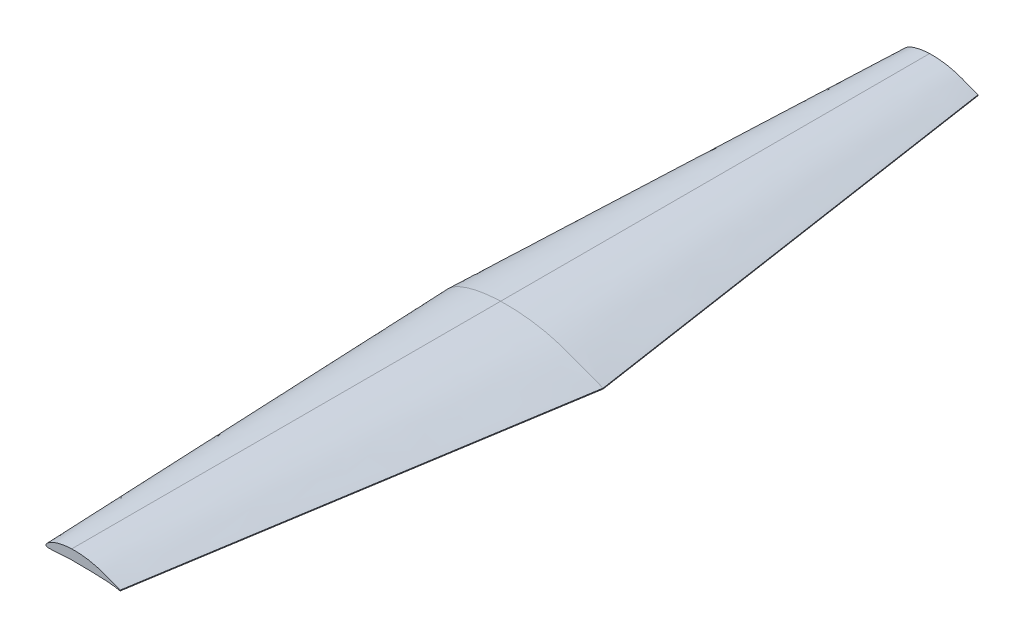
SolidWorks part; units mm, degrees
ref_plane "前视基准面" through (0, 0, 0) normal (0, 0, 1) x (1, 0, 0)
ref_plane "上视基准面" through (0, 0, 0) normal (0, 1, 0) x (1, 0, 0)
ref_plane "右视基准面" through (0, 0, 0) normal (1, 0, 0) x (0, 0, -1)
sketch "草图3" plane through (0, 0, 0) normal (0, 0, 1) x (1, 0, 0)
  line L0 (286.0556, -67.2093) -> (286.0556, -69.5328)
  spline S0 degree 3 poles (0, 0) (-2.7254, 0.1648) (-6.5293, -0.1383) (-11.397, -0.4053) (-15.7139, -0.6444) (-21.1219, -1.0416) (-27.6196, -1.6029) (-34.106, -2.271) (-40.5798, -3.0436) (-47.0383, -3.9317) (-53.4797, -4.936) (-58.8544, -5.8774) (-63.17, -6.7002) (-66.4344, -7.3579) (-69.692, -8.0463) (-72.9411, -8.7726) (-76.1832, -9.53) (-79.4172, -10.3236) (-82.6712, -11.1618) (-85.9452, -12.0414) (-89.2363, -12.971) (-92.5148, -13.9419) (-95.7791, -14.9599) (-99.0288, -16.0242) (-102.2624, -17.1403) (-104.9625, -18.1217) (-107.1365, -18.9452) (-108.7915, -19.5894) (-110.4392, -20.2501) (-112.0802, -20.926) (-113.4364, -21.5146) (-114.7996, -22.0847) (-116.4298, -22.8496) (-118.3603, -23.7346) (-120.2914, -24.6854) (-121.9485, -25.5247) (-123.5937, -26.392) (-125.2295, -27.284) (-126.8556, -28.2049) (-128.5172, -29.1774) (-130.2108, -30.2054) (-131.9305, -31.2916) (-133.6283, -32.4064) (-135.2985, -33.5465) (-136.9327, -34.7128) (-138.5277, -35.8993) (-139.8798, -36.9561) (-141.0061, -37.8695) (-141.9216, -38.6374) (-142.8307, -39.4252) (-143.7397, -40.2392) (-144.6561, -41.086) (-145.5864, -41.9717) (-146.6414, -43.0038) (-147.814, -44.1864) (-149.0511, -45.5345) (-150.1833, -46.9378) (-151.1378, -48.3803) (-151.8357, -49.854) (-152.198, -51.3579) (-152.1164, -52.6852) (-151.7365, -53.7579) (-151.2487, -54.6228) (-150.6211, -55.445) (-149.8757, -56.2108) (-149.0412, -56.9109) (-148.1414, -57.5317) (-147.2349, -58.0421) (-146.3423, -58.4466) (-145.4769, -58.7603) (-144.6033, -59.0093) (-143.7243, -59.2082) (-142.8393, -59.3636) (-141.9506, -59.4905) (-140.8259, -59.6225) (-139.4649, -59.7643) (-137.8658, -59.9018) (-136.2622, -60.0125) (-134.6556, -60.0983) (-133.0466, -60.1615) (-131.4364, -60.2023) (-129.8251, -60.2236) (-128.2132, -60.2252) (-126.6017, -60.2114) (-124.9913, -60.1828) (-123.3818, -60.1442) (-121.7725, -60.0943) (-120.1633, -60.0396) (-118.5533, -59.9787) (-116.4051, -59.8971) (-114.2563, -59.8096) (-112.1077, -59.7183) (-110.4961, -59.646) (-108.8842, -59.573) (-106.7339, -59.4685) (-104.0451, -59.3331) (-100.8189, -59.158) (-97.5935, -58.9743) (-94.369, -58.7831) (-91.1445, -58.5883) (-87.9195, -58.3917) (-84.6944, -58.1934) (-81.4687, -57.9986) (-78.2436, -57.8034) (-75.0185, -57.6121) (-71.7936, -57.4231) (-68.568, -57.2395) (-65.3421, -57.0559) (-60.8897, -56.812) (-50.4824, -56.2568) (-39.738, -55.7609) (-29.1456, -55.3181) (-23.4361, -55.1001) (-16.9891, -54.8712) (-10.5445, -54.6675) (-5.2161, -54.5116) (24.8162, -53.7512) (54.8641, -53.7858) (86.0077, -54.1717) (92.4374, -54.2674) (98.866, -54.378) (104.7346, -54.4925) (115.4929, -54.7248) (126.2066, -55.0005) (137.478, -55.3335) (143.8594, -55.5311) (149.2135, -55.7021) (153.497, -55.8457) (156.069, -55.93) (159.2825, -56.0398) (163.5676, -56.1844) (169.5643, -56.3927) (175.9899, -56.6246) (182.4135, -56.8749) (188.8353, -57.1505) (195.2555, -57.456) (201.6747, -57.8026) (208.0953, -58.1948) (214.5156, -58.6401) (220.934, -59.1451) (227.3471, -59.7063) (233.7544, -60.3361) (240.1564, -61.0305) (246.5529, -61.799) (251.8849, -62.5035) (256.1556, -63.107) (259.3661, -63.5886) (262.5702, -64.1028) (265.7667, -64.6553) (268.953, -65.255) (272.1283, -65.9071) (275.3111, -66.6228) (278.4998, -67.4069) (282.0905, -68.3717) (284.6152, -69.0618) (286.0556, -69.5328) knots 0 0 0 0 0.013429 0.018717 0.024004 0.034706 0.045405 0.056103 0.066798 0.077493 0.088187 0.098883 0.104347 0.10981 0.115272 0.120733 0.126196 0.131659 0.137123 0.142734 0.148344 0.153954 0.159562 0.165173 0.170784 0.176398 0.179312 0.182225 0.185139 0.188049 0.19096 0.192415 0.195321 0.199821 0.202867 0.205915 0.208964 0.21202 0.215085 0.218161 0.221496 0.224835 0.228171 0.231492 0.234788 0.238052 0.241275 0.243233 0.245189 0.247156 0.249154 0.251194 0.253297 0.255475 0.258458 0.261493 0.264477 0.267324 0.269988 0.272465 0.274861 0.276409 0.278031 0.279729 0.281486 0.283281 0.285082 0.286859 0.288394 0.2899 0.291385 0.292861 0.294334 0.295807 0.297279 0.299907 0.302541 0.305178 0.307818 0.31046 0.313103 0.315746 0.318391 0.321036 0.323677 0.326318 0.32896 0.331601 0.334243 0.33689 0.342182 0.344828 0.347475 0.350122 0.352769 0.358071 0.363372 0.368672 0.373971 0.379271 0.384571 0.389873 0.395175 0.400476 0.405775 0.411076 0.416376 0.421677 0.426979 0.438322 0.472972 0.479916 0.490502 0.501094 0.511666 0.522237 0.52733 0.659527 0.670078 0.680626 0.691176 0.701723 0.709516 0.744139 0.754471 0.765016 0.775562 0.780836 0.78611 0.788228 0.796661 0.807212 0.81776 0.828308 0.838852 0.849396 0.859942 0.870492 0.881056 0.891618 0.902179 0.91274 0.923304 0.933873 0.944448 0.949775 0.955101 0.960426 0.965747 0.971066 0.976383 0.9817 0.987121 0.992543 1 1 1 1
  spline S1 degree 3 poles (286.0556, -67.2093) (284.6443, -66.5978) (282.1755, -65.5473) (278.6409, -64.0767) (275.4746, -62.7904) (272.3122, -61.5438) (269.1569, -60.3294) (265.9937, -59.1363) (262.8244, -57.9585) (259.6502, -56.7935) (256.4744, -55.631) (252.2394, -54.0827) (246.9511, -52.1365) (240.6147, -49.781) (234.284, -47.4153) (227.9569, -45.0405) (221.6324, -42.6584) (215.3064, -40.2746) (208.9898, -37.8949) (202.6812, -35.5252) (196.3783, -33.1767) (190.0656, -30.8589) (183.9614, -28.6584) (179.5601, -27.1217) (176.6075, -26.0994) (174.2596, -25.3115) (170.1866, -23.92) (166.2258, -22.6238) (161.874, -21.285) (158.7366, -20.2915) (155.0668, -19.2273) (150.9749, -18.0061) (145.689, -16.5449) (139.3271, -14.8623) (132.9397, -13.2769) (126.5291, -11.7843) (120.1314, -10.3953) (113.7497, -9.1072) (107.3863, -7.9187) (101.0078, -6.8208) (94.6155, -5.8053) (88.2098, -4.8761) (81.7918, -4.0266) (75.3764, -3.2568) (68.9655, -2.5621) (62.5612, -1.9454) (56.1516, -1.404) (49.7366, -0.9395) (43.3162, -0.5533) (36.8905, -0.2441) (30.4575, -0.0157) (24.0193, 0.1343) (17.5776, 0.2001) (9.5705, 0.1861) (3.7124, 0.0371) (0, 0) knots 0 0 0 0 0.015566 0.027153 0.038744 0.050153 0.061555 0.072961 0.084369 0.095774 0.107181 0.118595 0.141408 0.164211 0.187011 0.209806 0.232607 0.255409 0.278224 0.30092 0.323611 0.346297 0.368978 0.389281 0.393477 0.4006 0.414345 0.437038 0.442772 0.460425 0.470342 0.481442 0.503641 0.525841 0.548041 0.570244 0.592452 0.614296 0.636131 0.657965 0.679798 0.701634 0.723471 0.745317 0.767026 0.788731 0.81043 0.832124 0.853822 0.875524 0.89723 0.918967 0.940698 0.962427 1 1 1 1
ref_plane "基准面6" through (0, 0, 1198) normal (0, 0, 1) x (1, 0, 0)
sketch "草图5" plane through (0, 0, 1198) normal (0, 0, 1) x (1, 0, 0)
  line L0 (135.2099, -32.178) -> (134.1595, -31.7343)
  line L1 (134.1595, -31.7343) -> (132.3785, -31.0014)
  line L2 (132.3785, -31.0014) -> (130.538, -30.2628)
  line L3 (130.538, -30.2628) -> (128.6487, -29.5234)
  line L4 (128.6487, -29.5234) -> (126.7095, -28.7801)
  line L5 (126.7095, -28.7801) -> (124.7288, -28.0303)
  line L6 (124.7288, -28.0303) -> (122.7145, -27.2731)
  line L7 (122.7145, -27.2731) -> (120.681, -26.5057)
  line L8 (120.681, -26.5057) -> (118.6366, -25.7333)
  line L9 (118.6366, -25.7333) -> (116.5882, -24.9552)
  line L10 (116.5882, -24.9552) -> (114.5327, -24.1718)
  line L11 (114.5327, -24.1718) -> (112.4767, -23.3864)
  line L12 (112.4767, -23.3864) -> (110.4226, -22.5988)
  line L13 (110.4226, -22.5988) -> (108.3692, -21.8105)
  line L14 (108.3692, -21.8105) -> (106.3231, -21.0245)
  line L15 (106.3231, -21.0245) -> (104.2886, -20.2409)
  line L16 (104.2886, -20.2409) -> (102.2624, -19.4627)
  line L17 (102.2624, -19.4627) -> (100.2393, -18.6847)
  line L18 (100.2393, -18.6847) -> (98.2143, -17.9078)
  line L19 (98.2143, -17.9078) -> (96.1873, -17.1346)
  line L20 (96.1873, -17.1346) -> (94.1685, -16.3685)
  line L21 (94.1685, -16.3685) -> (92.1597, -15.6135)
  line L22 (92.1597, -15.6135) -> (90.1625, -14.8708)
  line L23 (90.1625, -14.8708) -> (88.181, -14.1457)
  line L24 (88.181, -14.1457) -> (86.2061, -13.4369)
  line L25 (86.2061, -13.4369) -> (84.2421, -12.7442)
  line L26 (84.2421, -12.7442) -> (82.2899, -12.0718)
  line L27 (82.2899, -12.0718) -> (80.3415, -11.4207)
  line L28 (80.3415, -11.4207) -> (78.3954, -10.7857)
  line L29 (78.3954, -10.7857) -> (76.4548, -10.1739)
  line L30 (76.4548, -10.1739) -> (74.509, -9.5797)
  line L31 (74.509, -9.5797) -> (72.5628, -9.0033)
  line L32 (72.5628, -9.0033) -> (70.6155, -8.4473)
  line L33 (70.6155, -8.4473) -> (68.6635, -7.9102)
  line L34 (68.6635, -7.9102) -> (66.7063, -7.3907)
  line L35 (66.7063, -7.3907) -> (64.7481, -6.8897)
  line L36 (64.7481, -6.8897) -> (62.7857, -6.4088)
  line L37 (62.7857, -6.4088) -> (60.8187, -5.945)
  line L38 (60.8187, -5.945) -> (58.8481, -5.502)
  line L39 (58.8481, -5.502) -> (56.8722, -5.0759)
  line L40 (56.8722, -5.0759) -> (54.891, -4.67)
  line L41 (54.891, -4.67) -> (52.9027, -4.2816)
  line L42 (52.9027, -4.2816) -> (50.9072, -3.9113)
  line L43 (50.9072, -3.9113) -> (48.906, -3.5568)
  line L44 (48.906, -3.5568) -> (46.9012, -3.2218)
  line L45 (46.9012, -3.2218) -> (44.8875, -2.9037)
  line L46 (44.8875, -2.9037) -> (42.8649, -2.6024)
  line L47 (42.8649, -2.6024) -> (40.8378, -2.3156)
  line L48 (40.8378, -2.3156) -> (38.8054, -2.0458)
  line L49 (38.8054, -2.0458) -> (36.7699, -1.7907)
  line L50 (36.7699, -1.7907) -> (34.7309, -1.5534)
  line L51 (34.7309, -1.5534) -> (32.6898, -1.3307)
  line L52 (32.6898, -1.3307) -> (30.6467, -1.1252)
  line L53 (30.6467, -1.1252) -> (28.6014, -0.935)
  line L54 (28.6014, -0.935) -> (26.5583, -0.7623)
  line L55 (26.5583, -0.7623) -> (24.5119, -0.6066)
  line L56 (24.5119, -0.6066) -> (22.4653, -0.4651)
  line L57 (22.4653, -0.4651) -> (20.4208, -0.3423)
  line L58 (20.4208, -0.3423) -> (18.3735, -0.236)
  line L59 (18.3735, -0.236) -> (16.3292, -0.1453)
  line L60 (16.3292, -0.1453) -> (14.2863, -0.0737)
  line L61 (14.2863, -0.0737) -> (12.2413, -0.0176)
  line L62 (12.2413, -0.0176) -> (10.2028, 0.021)
  line L63 (10.2028, 0.021) -> (8.1626, 0.0399)
  line L64 (8.1626, 0.0399) -> (6.1247, 0.0438)
  line L65 (6.1247, 0.0438) -> (4.0913, 0.0283)
  line L66 (0.0002, 0) -> (-4.574, -0.0878)
  line L67 (-4.574, -0.0878) -> (-6.5869, -0.2357)
  line L68 (-6.5869, -0.2357) -> (-8.5967, -0.4036)
  line L69 (-8.5967, -0.4036) -> (-10.6009, -0.5882)
  line L70 (-10.6009, -0.5882) -> (-12.5959, -0.7929)
  line L71 (-12.5959, -0.7929) -> (-14.5847, -1.0176)
  line L72 (-14.5847, -1.0176) -> (-16.5631, -1.2611)
  line L73 (-16.5631, -1.2611) -> (-18.5329, -1.5264)
  line L74 (-18.5329, -1.5264) -> (-20.4942, -1.8124)
  line L75 (-20.4942, -1.8124) -> (-22.4457, -2.1198)
  line L76 (-22.4457, -2.1198) -> (-24.3887, -2.4489)
  line L77 (-24.3887, -2.4489) -> (-26.3213, -2.8001)
  line L78 (-26.3213, -2.8001) -> (-28.246, -3.1737)
  line L79 (-28.246, -3.1737) -> (-30.1572, -3.568)
  line L80 (-30.1572, -3.568) -> (-32.0588, -3.9874)
  line L81 (-32.0588, -3.9874) -> (-33.9481, -4.4282)
  line L82 (-33.9481, -4.4282) -> (-35.8246, -4.8922)
  line L83 (-35.8246, -4.8922) -> (-37.6857, -5.3777)
  line L84 (-37.6857, -5.3777) -> (-39.5304, -5.886)
  line L85 (-39.5304, -5.886) -> (-41.3497, -6.4123)
  line L86 (-41.3497, -6.4123) -> (-43.1433, -6.9624)
  line L87 (-43.1433, -6.9624) -> (-44.9092, -7.5318)
  line L88 (-44.9092, -7.5318) -> (-46.6407, -8.124)
  line L89 (-46.6407, -8.124) -> (-48.3382, -8.7359)
  line L90 (-48.3382, -8.7359) -> (-49.9933, -9.367)
  line L91 (-49.9933, -9.367) -> (-51.6046, -10.0187)
  line L92 (-51.6046, -10.0187) -> (-53.1677, -10.6886)
  line L93 (-53.1677, -10.6886) -> (-54.6759, -11.3734)
  line L94 (-54.6759, -11.3734) -> (-56.1242, -12.0786)
  line L95 (-56.1242, -12.0786) -> (-57.5169, -12.7992)
  line L96 (-57.5169, -12.7992) -> (-58.8452, -13.53)
  line L97 (-58.8452, -13.53) -> (-60.1046, -14.2643)
  line L98 (-60.1046, -14.2643) -> (-61.2879, -14.995)
  line L99 (-61.2879, -14.995) -> (-62.3893, -15.711)
  line L100 (-62.3893, -15.711) -> (-63.403, -16.4041)
  line L101 (-63.403, -16.4041) -> (-64.3262, -17.0669)
  line L102 (-64.3262, -17.0669) -> (-65.1602, -17.6981)
  line L103 (-65.1602, -17.6981) -> (-65.9115, -18.2938)
  line L104 (-65.9115, -18.2938) -> (-66.5852, -18.8526)
  line L105 (-66.5852, -18.8526) -> (-67.188, -19.3779)
  line L106 (-67.188, -19.3779) -> (-67.7286, -19.8695)
  line L107 (-67.7286, -19.8695) -> (-68.2151, -20.3272)
  line L108 (-68.2151, -20.3272) -> (-68.6531, -20.7544)
  line L109 (-68.6531, -20.7544) -> (-69.0499, -21.1521)
  line L110 (-69.0499, -21.1521) -> (-69.4107, -21.5226)
  line L111 (-69.4107, -21.5226) -> (-69.7393, -21.8688)
  line L112 (-69.7393, -21.8688) -> (-70.0357, -22.1958)
  line L113 (-70.0357, -22.1958) -> (-70.3046, -22.5077)
  line L114 (-70.3046, -22.5077) -> (-70.5464, -22.8063)
  line L115 (-70.5464, -22.8063) -> (-70.7632, -23.0946)
  line L116 (-70.7632, -23.0946) -> (-70.9581, -23.3731)
  line L117 (-70.9581, -23.3731) -> (-71.1318, -23.6437)
  line L118 (-71.1318, -23.6437) -> (-71.2825, -23.9083)
  line L119 (-71.2825, -23.9083) -> (-71.4114, -24.1681)
  line L120 (-71.4114, -24.1681) -> (-71.5209, -24.4223)
  line L121 (-71.5209, -24.4223) -> (-71.607, -24.673)
  line L122 (-71.607, -24.673) -> (-71.6701, -24.9201)
  line L123 (-71.6701, -24.9201) -> (-71.7126, -25.1617)
  line L124 (-71.7126, -25.1617) -> (-71.7297, -25.3981)
  line L125 (-71.7419, -26.2732) -> (-71.7313, -26.5109)
  line L126 (-71.7313, -26.5109) -> (-71.7066, -26.7514)
  line L127 (-71.7066, -26.7514) -> (-71.643, -26.9922)
  line L128 (-71.643, -26.9922) -> (-71.5522, -27.2309)
  line L129 (-71.5522, -27.2309) -> (-71.4348, -27.4661)
  line L130 (-71.4348, -27.4661) -> (-71.2913, -27.6966)
  line L131 (-71.2913, -27.6966) -> (-71.1242, -27.9218)
  line L132 (-71.1242, -27.9218) -> (-70.9347, -28.1427)
  line L133 (-70.9347, -28.1427) -> (-70.7222, -28.357)
  line L134 (-70.7222, -28.357) -> (-70.4873, -28.5647)
  line L135 (-70.4873, -28.5647) -> (-70.2312, -28.7687)
  line L136 (-70.2312, -28.7687) -> (-69.9508, -28.9618)
  line L137 (-69.9508, -28.9618) -> (-69.6441, -29.146)
  line L138 (-69.6441, -29.146) -> (-69.3124, -29.3192)
  line L139 (-69.3124, -29.3192) -> (-68.9512, -29.4774)
  line L140 (-68.9512, -29.4774) -> (-68.5579, -29.6138)
  line L141 (-68.5579, -29.6138) -> (-68.13, -29.7334)
  line L142 (-68.13, -29.7334) -> (-67.6657, -29.8321)
  line L143 (-67.6657, -29.8321) -> (-67.1588, -29.9118)
  line L144 (-67.1588, -29.9118) -> (-66.6046, -29.9789)
  line L145 (-66.6046, -29.9789) -> (-65.9964, -30.0367)
  line L146 (-65.9964, -30.0367) -> (-65.3258, -30.0916)
  line L147 (-65.3258, -30.0916) -> (-64.5847, -30.1409)
  line L148 (-64.5847, -30.1409) -> (-63.7613, -30.1792)
  line L149 (-63.7613, -30.1792) -> (-62.8437, -30.209)
  line L150 (-62.8437, -30.209) -> (-61.8202, -30.2238)
  line L151 (-61.8202, -30.2238) -> (-60.677, -30.2204)
  line L152 (-60.677, -30.2204) -> (-59.4023, -30.1954)
  line L153 (-59.4023, -30.1954) -> (-57.9793, -30.1444)
  line L154 (-57.9793, -30.1444) -> (-56.4027, -30.0733)
  line L155 (-56.4027, -30.0733) -> (-54.6743, -29.9838)
  line L156 (-54.6743, -29.9838) -> (-52.821, -29.8829)
  line L157 (-52.821, -29.8829) -> (-50.8703, -29.7687)
  line L158 (-50.8703, -29.7687) -> (-48.852, -29.6425)
  line L159 (-48.852, -29.6425) -> (-46.7771, -29.5009)
  line L160 (-46.7771, -29.5009) -> (-44.6574, -29.3509)
  line L161 (-44.6574, -29.3509) -> (-42.5042, -29.1922)
  line L162 (-42.5042, -29.1922) -> (-40.325, -29.0312)
  line L163 (-40.325, -29.0312) -> (-38.1346, -28.8687)
  line L164 (-38.1346, -28.8687) -> (-35.9406, -28.7076)
  line L165 (-35.9406, -28.7076) -> (-33.7485, -28.5496)
  line L166 (-33.7485, -28.5496) -> (-31.5578, -28.3952)
  line L167 (-31.5578, -28.3952) -> (-29.3678, -28.2444)
  line L168 (-29.3678, -28.2444) -> (-27.1792, -28.0973)
  line L169 (-27.1792, -28.0973) -> (-24.9926, -27.9545)
  line L170 (-24.9926, -27.9545) -> (-22.8085, -27.8159)
  line L171 (-22.8085, -27.8159) -> (-20.6302, -27.682)
  line L172 (-20.6302, -27.682) -> (-18.4502, -27.5538)
  line L173 (-18.4502, -27.5538) -> (-16.2741, -27.4291)
  line L174 (-16.2741, -27.4291) -> (-14.1006, -27.3111)
  line L175 (-14.1006, -27.3111) -> (-11.9254, -27.1957)
  line L176 (-11.9254, -27.1957) -> (-9.7583, -27.0855)
  line L177 (-9.7583, -27.0855) -> (-7.586, -26.9829)
  line L178 (-7.586, -26.9829) -> (-5.4112, -26.8817)
  line L179 (-5.4112, -26.8817) -> (-1.5179, -26.823)
  line L180 (-1.5179, -26.823) -> (0.048, -26.8072)
  line L181 (5.4895, -26.7808) -> (2.0479, -26.787)
  line L182 (5.4895, -26.7808) -> (7.6568, -26.7559)
  line L183 (7.6568, -26.7559) -> (9.822, -26.7351)
  line L184 (9.822, -26.7351) -> (11.9801, -26.7196)
  line L185 (11.9801, -26.7196) -> (14.1428, -26.7104)
  line L186 (14.1428, -26.7104) -> (16.3065, -26.7038)
  line L187 (16.3065, -26.7038) -> (18.4781, -26.7031)
  line L188 (18.4781, -26.7031) -> (20.65, -26.7056)
  line L189 (20.65, -26.7056) -> (22.829, -26.7146)
  line L190 (22.829, -26.7146) -> (25.0128, -26.7276)
  line L191 (25.0128, -26.7276) -> (27.1987, -26.745)
  line L192 (27.1987, -26.745) -> (29.3869, -26.7668)
  line L193 (29.3869, -26.7668) -> (31.5761, -26.793)
  line L194 (31.5761, -26.793) -> (33.7688, -26.8231)
  line L195 (33.7688, -26.8231) -> (35.9583, -26.8562)
  line L196 (35.9583, -26.8562) -> (38.1445, -26.8933)
  line L197 (38.1445, -26.8933) -> (40.326, -26.9352)
  line L198 (40.326, -26.9352) -> (42.5044, -26.98)
  line L199 (42.5044, -26.98) -> (44.6695, -27.0284)
  line L200 (44.6695, -27.0284) -> (46.829, -27.0802)
  line L201 (46.829, -27.0802) -> (48.9846, -27.1349)
  line L202 (48.9846, -27.1349) -> (51.1455, -27.1942)
  line L203 (51.1455, -27.1942) -> (53.3125, -27.2544)
  line L204 (53.3125, -27.2544) -> (55.4952, -27.3216)
  line L205 (55.4952, -27.3216) -> (57.6871, -27.39)
  line L206 (57.6871, -27.39) -> (59.8793, -27.4627)
  line L207 (59.8793, -27.4627) -> (62.0764, -27.5387)
  line L208 (62.0764, -27.5387) -> (64.2733, -27.616)
  line L209 (64.2733, -27.616) -> (66.4652, -27.6973)
  line L210 (66.4652, -27.6973) -> (68.6575, -27.7811)
  line L211 (68.6575, -27.7811) -> (70.846, -27.8653)
  line L212 (70.846, -27.8653) -> (73.0246, -27.9521)
  line L213 (73.0246, -27.9521) -> (75.1969, -28.041)
  line L214 (75.1969, -28.041) -> (77.3692, -28.1287)
  line L215 (77.3692, -28.1287) -> (79.5481, -28.2211)
  line L216 (79.5481, -28.2211) -> (81.7319, -28.3131)
  line L217 (81.7319, -28.3131) -> (83.9131, -28.408)
  line L218 (83.9131, -28.408) -> (86.0904, -28.5077)
  line L219 (86.0904, -28.5077) -> (88.2613, -28.6107)
  line L220 (88.2613, -28.6107) -> (90.419, -28.7186)
  line L221 (90.419, -28.7186) -> (92.5688, -28.8347)
  line L222 (92.5688, -28.8347) -> (94.7084, -28.9571)
  line L223 (94.7084, -28.9571) -> (96.834, -29.0886)
  line L224 (96.834, -29.0886) -> (98.9534, -29.2302)
  line L225 (98.9534, -29.2302) -> (101.0582, -29.381)
  line L226 (101.0582, -29.381) -> (103.1555, -29.5437)
  line L227 (103.1555, -29.5437) -> (105.2392, -29.718)
  line L228 (105.2392, -29.718) -> (107.3179, -29.9063)
  line L229 (107.3179, -29.9063) -> (109.3837, -30.1049)
  line L230 (109.3837, -30.1049) -> (111.4369, -30.3184)
  line L231 (111.4369, -30.3184) -> (113.4776, -30.5472)
  line L232 (113.4776, -30.5472) -> (115.5107, -30.7917)
  line L233 (115.5107, -30.7917) -> (117.5258, -31.0482)
  line L234 (117.5258, -31.0482) -> (119.5215, -31.3215)
  line L235 (119.5215, -31.3215) -> (121.4979, -31.6093)
  line L236 (121.4979, -31.6093) -> (123.4427, -31.9114)
  line L237 (123.4427, -31.9114) -> (125.3533, -32.2296)
  line L238 (125.3533, -32.2296) -> (127.2197, -32.5652)
  line L239 (127.2197, -32.5652) -> (129.0473, -32.9234)
  line L240 (129.0473, -32.9234) -> (130.8287, -33.3014)
  line L241 (130.8287, -33.3014) -> (132.565, -33.7047)
  line L242 (132.565, -33.7047) -> (134.2544, -34.1296)
  line L243 (134.2544, -34.1296) -> (135.2139, -34.3894)
  line L244 (2.0002, -0.0109) -> (4.0913, 0.0283)
  line L245 (2.0002, -0.0109) -> (2.0001, 0.0182)
  line L246 (-71.7419, -26.2732) -> (-71.7456, -25.984)
  line L247 (-71.7456, -25.984) -> (-71.7476, -25.7116)
  line L248 (-71.7476, -25.7116) -> (-71.7297, -25.3981)
  line L249 (135.2139, -34.3894) -> (135.2099, -32.178)
  line L250 (0.048, -26.8072) -> (0.0002, 0)
  line L251 (2.0002, -0.0109) -> (0.0002, 0)
  line L252 (2.0479, -26.787) -> (0.0479, -26.7905)
sketch "草图8" plane through (0, 0, 1198) normal (0, 0, 1) x (1, 0, 0)
  line L0 (135.2099, -32.178) -> (135.2139, -34.3894)
  spline S0 degree 3 poles (0, 0) (1.3642, -0.0436) (3.4051, 0.0318) (6.1262, 0.0463) (8.1634, 0.042) (10.2023, 0.0246) (12.2436, -0.0147) (14.2858, -0.0715) (16.3301, -0.1416) (18.3749, -0.2338) (20.4203, -0.3395) (22.4666, -0.4617) (24.5123, -0.6047) (26.5579, -0.7591) (28.6029, -0.9322) (30.6467, -1.1229) (32.6901, -1.3275) (34.731, -1.5513) (36.7699, -1.7872) (38.8053, -2.0438) (40.8373, -2.3121) (42.8644, -2.6002) (44.8859, -2.9001) (46.8996, -3.2188) (48.9065, -3.5531) (50.9067, -3.9089) (52.9022, -4.2779) (54.8904, -4.667) (56.8727, -5.0721) (58.8481, -5.4995) (60.8199, -5.9411) (62.7861, -6.4064) (64.7493, -6.886) (66.7082, -7.3883) (68.6642, -7.9072) (70.6166, -8.4443) (72.5653, -9.0004) (74.5113, -9.5775) (76.4558, -10.1711) (78.4005, -10.7833) (80.3444, -11.4198) (82.2944, -12.0695) (84.2485, -12.7438) (86.2116, -13.4371) (88.1855, -14.1447) (90.1696, -14.8715) (92.1648, -15.6143) (94.1731, -16.3688) (96.1907, -17.1354) (98.2144, -17.907) (100.239, -18.6842) (102.2631, -19.4636) (104.2919, -20.2413) (106.3265, -21.0265) (108.3716, -21.8113) (110.4227, -22.5988) (112.4767, -23.3872) (114.5323, -24.1718) (116.5854, -24.9545) (118.6344, -25.7336) (120.6774, -26.504) (122.7073, -27.2716) (124.7186, -28.0252) (126.6971, -28.7741) (128.6347, -29.5153) (130.525, -30.2543) (132.7145, -31.1334) (134.2701, -31.7764) (135.2099, -32.178) knots 0 0 0 0 0.029182 0.043684 0.058219 0.07277 0.087311 0.101901 0.11648 0.131075 0.145695 0.160303 0.174934 0.189572 0.204195 0.218844 0.23349 0.248133 0.262773 0.277404 0.292026 0.306627 0.321212 0.335751 0.350247 0.364743 0.379217 0.393666 0.40809 0.422505 0.43691 0.451323 0.465733 0.480149 0.494591 0.50903 0.523473 0.537949 0.55246 0.566971 0.581571 0.596222 0.610948 0.625801 0.640766 0.655814 0.671011 0.686316 0.701716 0.717189 0.732658 0.748116 0.763596 0.779145 0.794778 0.810464 0.826154 0.841851 0.857539 0.873167 0.888753 0.904255 0.919602 0.934707 0.949518 0.963988 0.978132 1 1 1 1
  spline S1 degree 3 poles (0, 0) (-2.2028, 0.0914) (-5.0669, -0.1072) (-8.5955, -0.4006) (-10.5988, -0.5844) (-12.5949, -0.7894) (-14.5824, -1.0142) (-16.5617, -1.2568) (-18.5316, -1.5228) (-20.4927, -1.8083) (-22.4447, -2.1157) (-24.3873, -2.4447) (-26.3209, -2.7959) (-28.2437, -3.1696) (-30.1568, -3.563) (-32.0572, -3.9834) (-33.9468, -4.4232) (-35.8224, -4.8877) (-37.6837, -5.3723) (-39.5251, -5.8809) (-41.3456, -6.4052) (-43.1379, -6.9567) (-44.903, -7.5234) (-46.6342, -8.117) (-48.3298, -8.7268) (-49.9851, -9.3575) (-51.5954, -10.0083) (-53.1563, -10.6778) (-54.6656, -11.3595) (-56.1141, -12.0669) (-57.5048, -12.785) (-58.8313, -13.5152) (-60.0886, -14.2475) (-61.2689, -14.9769) (-62.3683, -15.691) (-63.3804, -16.3832) (-64.3048, -17.045) (-65.1395, -17.6775) (-65.8919, -18.2737) (-66.5683, -18.8335) (-67.1727, -19.3606) (-67.7144, -19.854) (-68.2031, -20.3127) (-68.642, -20.7418) (-69.0403, -21.1406) (-69.4021, -21.5124) (-69.7326, -21.8587) (-70.0305, -22.1873) (-70.3002, -22.4994) (-70.5434, -22.7986) (-70.7607, -23.0879) (-70.9564, -23.3668) (-71.1313, -23.6374) (-71.2828, -23.9026) (-71.4114, -24.1632) (-71.5229, -24.4172) (-71.6097, -24.6688) (-71.6716, -24.9164) (-71.7183, -25.1583) (-71.7292, -25.4239) (-71.7529, -25.6976) (-71.744, -25.9896) (-71.7445, -26.2562) (-71.7322, -26.5121) (-71.7145, -26.7552) (-71.6455, -26.9954) (-71.5554, -27.2349) (-71.437, -27.4707) (-71.2927, -27.7012) (-71.1244, -27.9265) (-70.935, -28.1478) (-70.7218, -28.3624) (-70.4851, -28.5692) (-70.2304, -28.7749) (-69.9478, -28.9678) (-69.641, -29.1517) (-69.3083, -29.3259) (-68.9466, -29.4856) (-68.5501, -29.6201) (-68.1214, -29.7409) (-67.6539, -29.8388) (-67.1443, -29.9167) (-66.5874, -29.9835) (-65.9759, -30.0394) (-65.3027, -30.0952) (-64.5577, -30.1454) (-63.7301, -30.182) (-62.8086, -30.2132) (-61.7803, -30.2271) (-60.633, -30.2231) (-59.3525, -30.1981) (-57.9278, -30.1441) (-56.3518, -30.073) (-54.6326, -29.9817) (-52.7883, -29.8829) (-50.8475, -29.7682) (-48.8327, -29.6439) (-46.762, -29.5001) (-44.646, -29.3517) (-42.4956, -29.1911) (-40.3212, -29.0313) (-38.1335, -28.8683) (-35.9413, -28.7072) (-33.7491, -28.549) (-31.5582, -28.3946) (-29.3684, -28.2439) (-27.18, -28.0967) (-24.9936, -27.9539) (-22.8106, -27.8154) (-20.6298, -27.6808) (-18.4516, -27.5537) (-16.2752, -27.4276) (-14.1001, -27.311) (-11.9282, -27.1954) (-9.7568, -27.0827) (-7.5851, -26.9867) (-4.8402, -26.8366) (-2.2937, -26.8327) (0.1926, -26.8062) (2.5284, -26.7758) (5.0649, -26.7938) (7.6561, -26.7533) (9.8196, -26.7349) (11.9816, -26.718) (14.1431, -26.7105) (16.3091, -26.7022) (18.4782, -26.7031) (20.6524, -26.7041) (22.8306, -26.7142) (25.0135, -26.7267) (27.1995, -26.7443) (29.3873, -26.7661) (31.5773, -26.7924) (33.7678, -26.8227) (35.9572, -26.8554) (38.143, -26.8924) (40.325, -26.9349) (42.5, -26.9792) (44.6677, -27.0277) (46.8277, -27.0799) (48.9864, -27.1337) (51.1475, -27.1948) (53.3178, -27.2526) (55.4982, -27.3223) (57.6873, -27.3889) (59.881, -27.4622) (62.0764, -27.5388) (64.2717, -27.6149) (66.4654, -27.6969) (68.6562, -27.7812) (70.8428, -27.8646) (73.0226, -27.9514) (75.1968, -28.0419) (77.3715, -28.1273) (79.5497, -28.2218) (81.7311, -28.3123) (83.9119, -28.407) (86.0884, -28.5071) (88.257, -28.6097) (90.4166, -28.7167) (92.5656, -28.8337) (94.704, -28.955) (96.8323, -29.0867) (98.9488, -29.2284) (101.0562, -29.3786) (103.1514, -29.5414) (105.2382, -29.7152) (107.3141, -29.9044) (109.3803, -30.1017) (111.4336, -30.3153) (113.476, -30.544) (115.5055, -30.7892) (117.5207, -31.0437) (119.5162, -31.3182) (121.4888, -31.6047) (123.433, -31.9063) (125.3407, -32.2234) (127.2096, -32.5579) (129.0347, -32.9165) (130.8176, -33.2923) (132.8757, -33.7722) (134.3354, -34.1442) (135.2139, -34.3894) knots 0 0 0 0 0.022815 0.029794 0.036759 0.043698 0.050624 0.057522 0.0644 0.071259 0.078095 0.084914 0.091711 0.098496 0.105249 0.111987 0.118701 0.12539 0.132046 0.138667 0.145221 0.151712 0.158133 0.164465 0.170709 0.176839 0.182853 0.188738 0.19447 0.200044 0.205471 0.210717 0.215761 0.220574 0.22512 0.229369 0.233302 0.236921 0.240239 0.243268 0.246035 0.248564 0.250875 0.252992 0.254936 0.256726 0.258377 0.259905 0.261329 0.262659 0.263907 0.265084 0.266196 0.26725 0.268253 0.269211 0.270129 0.271011 0.27186 0.27268 0.273767 0.27471 0.27571 0.276534 0.27737 0.278232 0.279116 0.280026 0.280965 0.281935 0.282943 0.283987 0.285072 0.286205 0.287383 0.288621 0.289916 0.29128 0.292721 0.294258 0.295901 0.297677 0.299608 0.301722 0.304051 0.306621 0.309474 0.31265 0.316193 0.320149 0.32456 0.329488 0.334949 0.340938 0.347361 0.354122 0.36112 0.368317 0.37567 0.383141 0.390703 0.398303 0.405916 0.413521 0.421121 0.428717 0.436308 0.44389 0.451463 0.459015 0.466572 0.474115 0.481647 0.489185 0.496693 0.504219 0.511753 0.525227 0.530645 0.537567 0.549476 0.556976 0.564469 0.571937 0.579421 0.586908 0.594423 0.601939 0.609479 0.617036 0.6246 0.632173 0.639749 0.647337 0.654915 0.662481 0.670031 0.677571 0.685065 0.69254 0.700001 0.707482 0.714983 0.72254 0.730129 0.737719 0.745326 0.752933 0.760523 0.768115 0.775694 0.783239 0.790762 0.798285 0.805832 0.813395 0.82095 0.828493 0.836013 0.843489 0.850939 0.858355 0.865725 0.873075 0.880377 0.887656 0.894892 0.902115 0.909296 0.91644 0.923545 0.930631 0.937661 0.944631 0.951543 0.958353 0.965056 0.971618 0.978062 0.984364 0.990532 1 1 1 1
loft "放样2" add profiles "草图8", "草图3"
sketch "草图9" plane through (0, 0, 0) normal (0, 0, 1) x (1, 0, 0)
  line L0 (286.0556, -67.2093) -> (286.0556, -69.5328)
  spline S0 degree 3 poles (0, 0) (-2.7254, 0.1648) (-6.5293, -0.1383) (-11.397, -0.4053) (-15.7139, -0.6444) (-21.1219, -1.0416) (-27.6196, -1.6029) (-34.106, -2.271) (-40.5798, -3.0436) (-47.0383, -3.9317) (-53.4797, -4.936) (-58.8544, -5.8774) (-63.17, -6.7002) (-66.4344, -7.3579) (-69.692, -8.0463) (-72.9411, -8.7726) (-76.1832, -9.53) (-79.4172, -10.3236) (-82.6712, -11.1618) (-85.9452, -12.0414) (-89.2363, -12.971) (-92.5148, -13.9419) (-95.7791, -14.9599) (-99.0288, -16.0242) (-102.2624, -17.1403) (-104.9625, -18.1217) (-107.1365, -18.9452) (-108.7915, -19.5894) (-110.4392, -20.2501) (-112.0802, -20.926) (-113.4364, -21.5146) (-114.7996, -22.0847) (-116.4298, -22.8496) (-118.3603, -23.7346) (-120.2914, -24.6854) (-121.9485, -25.5247) (-123.5937, -26.392) (-125.2295, -27.284) (-126.8556, -28.2049) (-128.5172, -29.1774) (-130.2108, -30.2054) (-131.9305, -31.2916) (-133.6283, -32.4064) (-135.2985, -33.5465) (-136.9327, -34.7128) (-138.5277, -35.8993) (-139.8798, -36.9561) (-141.0061, -37.8695) (-141.9216, -38.6374) (-142.8307, -39.4252) (-143.7397, -40.2392) (-144.6561, -41.086) (-145.5864, -41.9717) (-146.6414, -43.0038) (-147.814, -44.1864) (-149.0511, -45.5345) (-150.1833, -46.9378) (-151.1378, -48.3803) (-151.8357, -49.854) (-152.198, -51.3579) (-152.1164, -52.6852) (-151.7365, -53.7579) (-151.2487, -54.6228) (-150.6211, -55.445) (-149.8757, -56.2108) (-149.0412, -56.9109) (-148.1414, -57.5317) (-147.2349, -58.0421) (-146.3423, -58.4466) (-145.4769, -58.7603) (-144.6033, -59.0093) (-143.7243, -59.2082) (-142.8393, -59.3636) (-141.9506, -59.4905) (-140.8259, -59.6225) (-139.4649, -59.7643) (-137.8658, -59.9018) (-136.2622, -60.0125) (-134.6556, -60.0983) (-133.0466, -60.1615) (-131.4364, -60.2023) (-129.8251, -60.2236) (-128.2132, -60.2252) (-126.6017, -60.2114) (-124.9913, -60.1828) (-123.3818, -60.1442) (-121.7725, -60.0943) (-120.1633, -60.0396) (-118.5533, -59.9787) (-116.4051, -59.8971) (-114.2563, -59.8096) (-112.1077, -59.7183) (-110.4961, -59.646) (-108.8842, -59.573) (-106.7339, -59.4685) (-104.0451, -59.3331) (-100.8189, -59.158) (-97.5935, -58.9743) (-94.369, -58.7831) (-91.1445, -58.5883) (-87.9195, -58.3917) (-84.6944, -58.1934) (-81.4687, -57.9986) (-78.2436, -57.8034) (-75.0185, -57.6121) (-71.7936, -57.4231) (-68.568, -57.2395) (-65.3421, -57.0559) (-60.8897, -56.812) (-50.4824, -56.2568) (-39.738, -55.7609) (-29.1456, -55.3181) (-23.4361, -55.1001) (-16.9891, -54.8712) (-10.5445, -54.6675) (-5.2161, -54.5116) (24.8162, -53.7512) (54.8641, -53.7858) (86.0077, -54.1717) (92.4374, -54.2674) (98.866, -54.378) (104.7346, -54.4925) (115.4929, -54.7248) (126.2066, -55.0005) (137.478, -55.3335) (143.8594, -55.5311) (149.2135, -55.7021) (153.497, -55.8457) (156.069, -55.93) (159.2825, -56.0398) (163.5676, -56.1844) (169.5643, -56.3927) (175.9899, -56.6246) (182.4135, -56.8749) (188.8353, -57.1505) (195.2555, -57.456) (201.6747, -57.8026) (208.0953, -58.1948) (214.5156, -58.6401) (220.934, -59.1451) (227.3471, -59.7063) (233.7544, -60.3361) (240.1564, -61.0305) (246.5529, -61.799) (251.8849, -62.5035) (256.1556, -63.107) (259.3661, -63.5886) (262.5702, -64.1028) (265.7667, -64.6553) (268.953, -65.255) (272.1283, -65.9071) (275.3111, -66.6228) (278.4998, -67.4069) (282.0905, -68.3717) (284.6152, -69.0618) (286.0556, -69.5328) knots 0 0 0 0 0.013429 0.018717 0.024004 0.034706 0.045405 0.056103 0.066798 0.077493 0.088187 0.098883 0.104347 0.10981 0.115272 0.120733 0.126196 0.131659 0.137123 0.142734 0.148344 0.153954 0.159562 0.165173 0.170784 0.176398 0.179312 0.182225 0.185139 0.188049 0.19096 0.192415 0.195321 0.199821 0.202867 0.205915 0.208964 0.21202 0.215085 0.218161 0.221496 0.224835 0.228171 0.231492 0.234788 0.238052 0.241275 0.243233 0.245189 0.247156 0.249154 0.251194 0.253297 0.255475 0.258458 0.261493 0.264477 0.267324 0.269988 0.272465 0.274861 0.276409 0.278031 0.279729 0.281486 0.283281 0.285082 0.286859 0.288394 0.2899 0.291385 0.292861 0.294334 0.295807 0.297279 0.299907 0.302541 0.305178 0.307818 0.31046 0.313103 0.315746 0.318391 0.321036 0.323677 0.326318 0.32896 0.331601 0.334243 0.33689 0.342182 0.344828 0.347475 0.350122 0.352769 0.358071 0.363372 0.368672 0.373971 0.379271 0.384571 0.389873 0.395175 0.400476 0.405775 0.411076 0.416376 0.421677 0.426979 0.438322 0.472972 0.479916 0.490502 0.501094 0.511666 0.522237 0.52733 0.659527 0.670078 0.680626 0.691176 0.701723 0.709516 0.744139 0.754471 0.765016 0.775562 0.780836 0.78611 0.788228 0.796661 0.807212 0.81776 0.828308 0.838852 0.849396 0.859942 0.870492 0.881056 0.891618 0.902179 0.91274 0.923304 0.933873 0.944448 0.949775 0.955101 0.960426 0.965747 0.971066 0.976383 0.9817 0.987121 0.992543 1 1 1 1
  spline S1 degree 3 poles (286.0556, -67.2093) (284.6443, -66.5978) (282.1755, -65.5473) (278.6409, -64.0767) (275.4746, -62.7904) (272.3122, -61.5438) (269.1569, -60.3294) (265.9937, -59.1363) (262.8244, -57.9585) (259.6502, -56.7935) (256.4744, -55.631) (252.2394, -54.0827) (246.9511, -52.1365) (240.6147, -49.781) (234.284, -47.4153) (227.9569, -45.0405) (221.6324, -42.6584) (215.3064, -40.2746) (208.9898, -37.8949) (202.6812, -35.5252) (196.3783, -33.1767) (190.0656, -30.8589) (183.9614, -28.6584) (179.5601, -27.1217) (176.6075, -26.0994) (174.2596, -25.3115) (170.1866, -23.92) (166.2258, -22.6238) (161.874, -21.285) (158.7366, -20.2915) (155.0668, -19.2273) (150.9749, -18.0061) (145.689, -16.5449) (139.3271, -14.8623) (132.9397, -13.2769) (126.5291, -11.7843) (120.1314, -10.3953) (113.7497, -9.1072) (107.3863, -7.9187) (101.0078, -6.8208) (94.6155, -5.8053) (88.2098, -4.8761) (81.7918, -4.0266) (75.3764, -3.2568) (68.9655, -2.5621) (62.5612, -1.9454) (56.1516, -1.404) (49.7366, -0.9395) (43.3162, -0.5533) (36.8905, -0.2441) (30.4575, -0.0157) (24.0193, 0.1343) (17.5776, 0.2001) (9.5705, 0.1861) (3.7124, 0.0371) (0, 0) knots 0 0 0 0 0.015566 0.027153 0.038744 0.050153 0.061555 0.072961 0.084369 0.095774 0.107181 0.118595 0.141408 0.164211 0.187011 0.209806 0.232607 0.255409 0.278224 0.30092 0.323611 0.346297 0.368978 0.389281 0.393477 0.4006 0.414345 0.437038 0.442772 0.460425 0.470342 0.481442 0.503641 0.525841 0.548041 0.570244 0.592452 0.614296 0.636131 0.657965 0.679798 0.701634 0.723471 0.745317 0.767026 0.788731 0.81043 0.832124 0.853822 0.875524 0.89723 0.918967 0.940698 0.962427 1 1 1 1
  point P3 (0, 0)
  point P5 (0, 0)
mirror "镜向5" about plane through (-17.6513, -54.8977, 0) normal (0, 0, -1) of "放样2"
